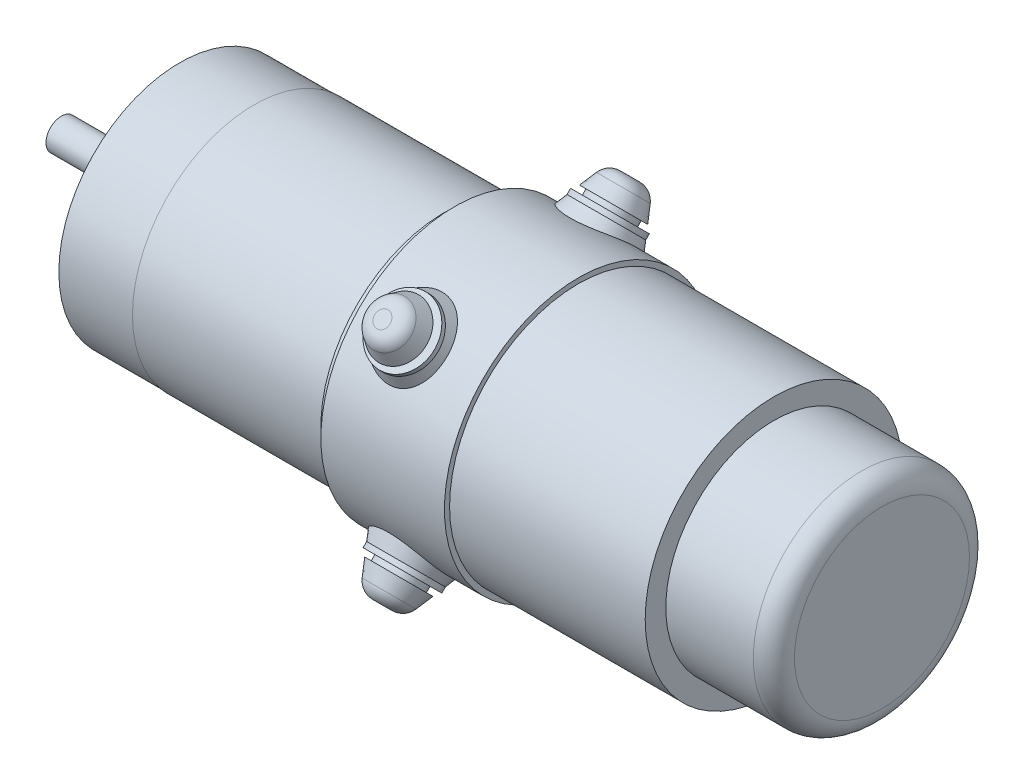
SolidWorks part; units mm, degrees
material "Acier non allié"
ref_plane "Plan1" through (0, 0, 0) normal (0, 0, 1) x (1, 0, 0)
ref_plane "Plan2" through (0, 0, 0) normal (0, 1, 0) x (1, 0, 0)
ref_plane "Plan3" through (0, 0, 0) normal (1, 0, 0) x (0, 0, -1)
sketch "Esquisse1" plane through (0, 0, 0) normal (0, 0, 1) x (1, 0, 0)
  line L0 (0, 0) -> (0, 17)
  line L1 (-4, 21) -> (-21, 21)
  line L2 (-139.4, 3) -> (-159.4, 3)
  line L3 (-159.4, 3) -> (-159.4, 0)
  line L4 (-159.4, 0) -> (-134.2475, 0)
  line L5 (-59, 25) -> (-59, 26)
  line L6 (-59, 26) -> (-83, 26)
  line L7 (-4.2299, 0) -> (-4.2299, 17)
  line L8 (-21, 21) -> (-21, 25)
  line L9 (-21, 25) -> (-59, 25)
  line L10 (-83, 26) -> (-83, 24)
  line L11 (-83, 24) -> (-85, 24)
  line L12 (-85, 24) -> (-85, 23.6)
  line L13 (-85, 23.6) -> (-122, 23.6)
  line L14 (-122, 23.6) -> (-122, 23.5)
  line L15 (-122, 23.5) -> (-136.4, 23.5)
  line L16 (-4.2299, 17) -> (-24.6821, 17)
  line L17 (-24.6821, 17) -> (-24.6821, 21)
  line L18 (-136.4, 23.5) -> (-136.4, 12.5)
  line L19 (0, 0) -> (-210.505, 0) construction
  line L20 (-136.4, 12.5) -> (-139.4, 12.5)
  line L21 (-139.4, 12.5) -> (-139.4, 3)
  line L22 (-24.6821, 21) -> (-134.2475, 21)
  line L23 (-134.2475, 21) -> (-134.2475, 0)
  line L26 (0, 0) -> (-4.2299, 0)
  arc A0 (0, 17) -> (-4, 21) centre (-4, 17) ccw
  dimension "D19" = 4
  dimension "D1" = 21
  dimension "D2" = 21
  dimension "D3" = 37
  dimension "D4" = 3
  dimension "D5" = 20
  dimension "D6" = 26
  dimension "D7" = 38
  dimension "D9" = 62
  dimension "D10" = 2
  dimension "D12" = 115.4
  dimension "D13" = 25
  dimension "D14" = 23.6
  dimension "D15" = 23.5
  dimension "D18" = 24
  dimension "D20" = 12.5
  dimension "D21" = 3
revolve "Base-Révolution" add sketch "Esquisse1" angle 360 about L19
ref_plane "Plan4" through (0, 0, 0) normal (0, 0.7071, 0.7071) x (-1, 0, 0)
ref_plane "Plan5" through (0, 24.0416, 24.0416) normal (0, 0.7071, 0.7071) x (-1, 0, 0)
sketch "Esquisse3" plane through (0, 24.0416, 24.0416) normal (0, 0.7071, 0.7071) x (-1, 0, 0)
  line L0 (0, 0) -> (210.505, 0) construction
  line L1 (83, -25) -> (83, 25) construction
  circle A0 centre (73, 0) radius 3.5
  dimension "D1" = 7
  dimension "D2" = 10
extrude "Boss.-Extru.2" add sketch "Esquisse3" against normal up to next draft 23 draft outward yes
fillet "Congé1" radius 3 1 edges at (-73, 21.5668, 26.5165)
ref_plane "Plan6" through (0, 20.1525, 20.1525) normal (0, 0.7071, 0.7071) x (-1, 0, 0)
sketch "Esquisse4" plane through (0, 20.1525, 20.1525) normal (0, 0.7071, 0.7071) x (-1, 0, 0)
  circle A0 centre (73, 0) radius 6.25
  circle A1 centre (73, 0) radius 4.2759 construction
  dimension "D1" = 12.5
extrude "Boss.-Extru.3" add sketch "Esquisse4" against normal up to next
sketch "Esquisse5" plane through (0, 20.1525, 20.1525) normal (0, 0.7071, 0.7071) x (-1, 0, 0)
  circle A0 centre (73, 0) radius 5.8346
  circle A1 centre (73, 0) radius 5.8346 construction
  circle A2 centre (73, 0) radius 4.38
  dimension "D1" = 8.76
extrude "Enlèv. mat.-Extru.1" cut sketch "Esquisse5" along normal blind 1
pattern_circular "Répétition circulaire1" count 4 every 90 about axis through (0, 0, 0) along (1, 0, 0) of "Enlèv. mat.-Extru.1", "Boss.-Extru.3", "Congé1", "Boss.-Extru.2"
hole_wizard "Trou taraudé M41" positions "Esquisse7" profile "Esquisse6" tap size "M4" standard "ISO"
sketch "Esquisse7" plane through (-136.4, 0, 0) normal (-1, 0, 0) x (0, 0, 1)
  line L0 (18.3848, 18.3848) -> (19.4606, 19.4606) construction
  circle A0 centre (0, 0) radius 18 construction
  point P0 (12.7279, 12.7279)
  dimension "D1" = 36
sketch "Esquisse6" plane through (-136.4, 12.7279, 12.7279) normal (0, 1, 0) x (0, 0, 1)
  line L0 (0, 0) -> (0, 9.4914)
  line L1 (0, 9.4914) -> (1.65, 8.5)
  line L2 (1.65, 8.5) -> (1.65, 0)
  line L5 (1.65, 0) -> (0, 0)
  line L10 (0, 9.4914) -> (-1.65, 8.5) construction
  line L11 (0, -6.35) -> (0, 107.95) construction
  dimension "Diamètre du trou pour taraudage" = 3.3
  dimension "Profondeur du trou pour taraudage" = 8.5
  dimension "Angle de pointe" = 118
cosmetic thread "Représentation de filetage1" parameters "D1"=4, "D2"=4
pattern_circular "Répétition circulaire2" count 4 over 360 about axis through (0, 0, 0) along (1, 0, 0) of "Trou taraudé M41"
